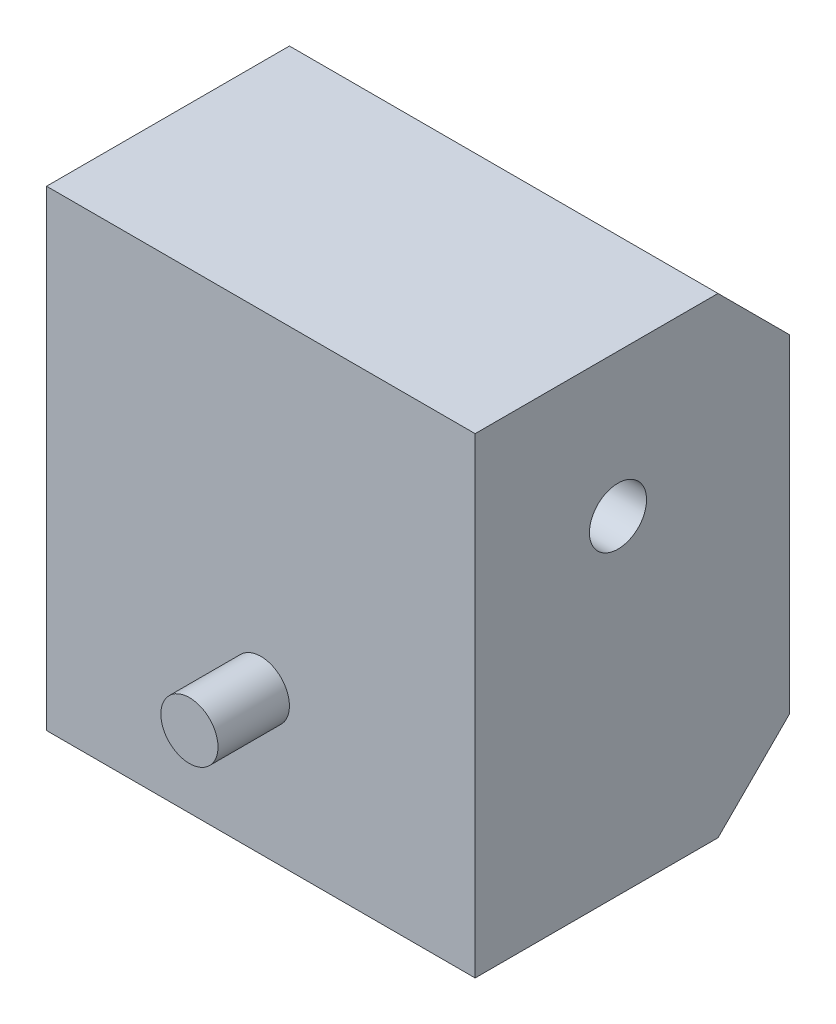
SolidWorks part; units mm, degrees
ref_plane "Alzado" through (0, 0, 0) normal (0, 0, 1) x (1, 0, 0)
ref_plane "Planta" through (0, 0, 0) normal (0, 1, 0) x (1, 0, 0)
ref_plane "Vista lateral" through (0, 0, 0) normal (1, 0, 0) x (0, 0, -1)
sketch "Croquis1" plane through (0, 0, 0) normal (0, 0, 1) x (1, 0, 0)
  line L1 (-15.1661, 12.0664) -> (14.8339, 12.0664)
  line L2 (-15.1661, 12.0664) -> (-15.1661, -20.9336)
  line L3 (-15.1661, -20.9336) -> (14.8339, -20.9336)
  line L4 (14.8339, 12.0664) -> (14.8339, -20.9336)
  dimension "D1" = 30
  dimension "D2" = 33
extrude "Saliente-Extruir1" add sketch "Croquis1" along normal blind 22
sketch "Croquis2" plane through (0, 0, 22) normal (0, 0, 1) x (1, 0, 0)
  line L1 (-15.1661, 12.0664) -> (-15.1661, -20.9336) construction
  line L3 (-15.1661, -20.9336) -> (14.8339, -20.9336) construction
  circle A1 centre (-0.1661, -10.9336) radius 2
  dimension "D1" = 15
  dimension "D2" = 4
  dimension "D5" = 10
sketch "Croquis3" plane through (14.8339, 0, 0) normal (1, 0, 0) x (0, 0, -1)
  line L0 (-22, -20.9336) -> (-22, 12.0664) construction
  line L1 (-22, 12.0664) -> (0, 12.0664) construction
  circle A0 centre (-12, 2.0664) radius 2
  dimension "D1" = 4
  dimension "D2" = 10
  dimension "D3" = 10
chamfer "Chaflán1" distance 5 angle 45 1 edges at (-0.1661, 12.0664, 0)
chamfer "Chaflán2" distance 5 angle 45 1 edges at (-0.1661, -20.9336, 0)
extrude "Cortar-Extruir1" cut sketch "Croquis3" against normal blind 35
extrude "Saliente-Extruir2" add sketch "Croquis2" along normal blind 5 contours A1
